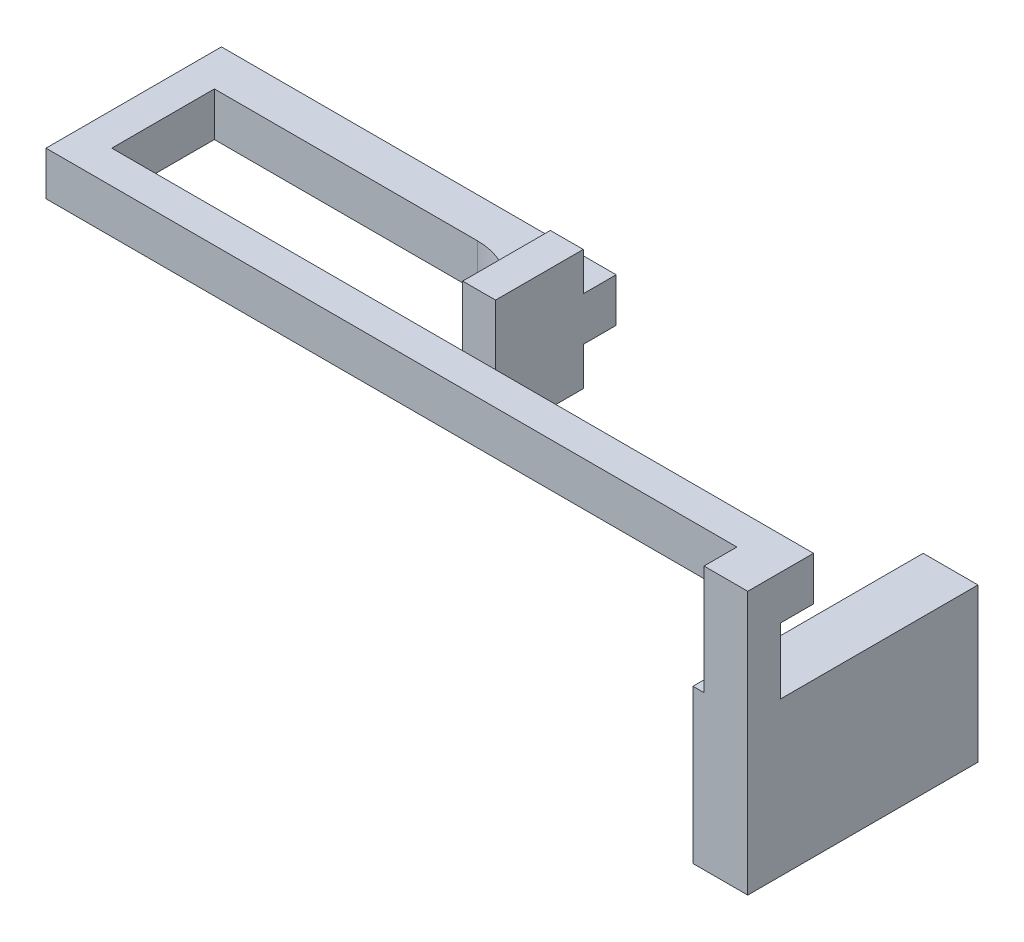
SolidWorks part; units mm, degrees
ref_plane "Front" through (0, 0, 0) normal (0, 0, 1) x (1, 0, 0)
ref_plane "Top" through (0, 0, 0) normal (0, 1, 0) x (1, 0, 0)
ref_plane "Right" through (0, 0, 0) normal (1, 0, 0) x (0, 0, -1)
sketch "Sketch1" plane through (0, 0, 0) normal (0, 0, 1) x (1, 0, 0)
  line L1 (0, 0) -> (-81.28, 0)
  line L2 (0, 0) -> (0, 5.08)
  line L3 (0, 5.08) -> (-81.28, 5.08)
  line L4 (-81.28, 0) -> (-81.28, 5.08)
  dimension "D1" = 5.08
  dimension "D2" = 81.28
extrude "Boss-Extrude1" add sketch "Sketch1" along normal blind 3.81
sketch "Sketch3" plane through (0, 5.08, 0) normal (0, 1, 0) x (1, 0, 0)
  line L1 (0, -3.81) -> (-5.0675, -3.81)
  line L2 (0, -3.81) -> (0, -7.62)
  line L3 (0, -7.62) -> (-5.0675, -7.62)
  line L4 (-5.0675, -3.81) -> (-5.0675, -7.62)
  line L5 (0, -3.81) -> (-81.28, -3.81) construction
  dimension "D1" = 3.81
extrude "Boss-Extrude2" add sketch "Sketch3" against normal blind 30.48
sketch "Sketch4" plane through (0, 0, 0) normal (1, 0, 0) x (0, 0, -1)
  line L1 (-7.62, -25.4) -> (19.05, -25.4)
  line L2 (-7.62, -25.4) -> (-7.62, -7.62)
  line L3 (-7.62, -7.62) -> (19.05, -7.62)
  line L4 (19.05, -25.4) -> (19.05, -7.62)
  dimension "D1" = 26.67
  dimension "D2" = 17.78
extrude "Boss-Extrude3" add sketch "Sketch4" against normal blind 6.35
sketch "Sketch6" plane through (-81.28, 0, 0) normal (-1, 0, 0) x (0, 0, 1)
  line L0 (3.81, 0) -> (0, 0) construction
  line L1 (3.81, 5.08) -> (-16.51, 5.08)
  line L2 (3.81, 5.08) -> (3.81, 0)
  line L3 (3.81, 0) -> (-16.51, 0)
  line L4 (-16.51, 5.08) -> (-16.51, 0)
  dimension "D1" = 20.32
extrude "Boss-Extrude4" add sketch "Sketch6" along normal blind 3.81
sketch "Sketch7" plane through (-81.28, 0, 0) normal (1, 0, 0) x (0, 0, -1)
  line L0 (16.51, 0) -> (0, 0) construction
  line L1 (16.51, 5.08) -> (11.8836, 5.08)
  line L2 (16.51, 5.08) -> (16.51, 0)
  line L3 (16.51, 0) -> (11.8836, 0)
  line L4 (11.8836, 5.08) -> (11.8836, 0)
extrude "Boss-Extrude5" add sketch "Sketch7" along normal blind 38.1
sketch "Sketch8" plane through (-43.18, 0, 0) normal (1, 0, 0) x (0, 0, -1)
  line L0 (0, 5.08) -> (0, 0) construction
  line L1 (2.54, -4.445) -> (16.51, -4.445)
  line L2 (2.54, -4.445) -> (2.54, 9.525)
  line L3 (2.54, 9.525) -> (16.51, 9.525)
  line L4 (16.51, -4.445) -> (16.51, 9.525)
  line L5 (9.525, -4.445) -> (9.525, 9.525) construction
  line L6 (16.51, 2.54) -> (9.525, 2.54) construction
  line L7 (11.8836, 5.08) -> (11.8836, 0) construction
  point P12 (11.8836, 2.54)
  dimension "D1" = 2.54
  dimension "D2" = 13.97
  dimension "D3" = 13.97
extrude "Boss-Extrude6" add sketch "Sketch8" along normal blind 3.81
sketch "Sketch9" plane through (-39.37, 0, 0) normal (1, 0, 0) x (0, 0, -1)
  line L1 (16.51, -4.445) -> (12.7, -4.445)
  line L2 (16.51, -4.445) -> (16.51, 0)
  line L3 (16.51, 0) -> (12.7, 0)
  line L4 (12.7, -4.445) -> (12.7, 0)
  line L5 (16.51, 9.525) -> (12.7, 9.525)
  line L6 (16.51, 9.525) -> (16.51, 5.08)
  line L7 (16.51, 5.08) -> (12.7, 5.08)
  line L8 (12.7, 9.525) -> (12.7, 5.08)
  dimension "D1" = 5.08
  dimension "D2" = 3.81
extrude "Cut-Extrude1" cut sketch "Sketch9" against normal through all
fillet "Fillet1" radius 7.62 1 edges at (-43.18, 2.54, -11.8836)
